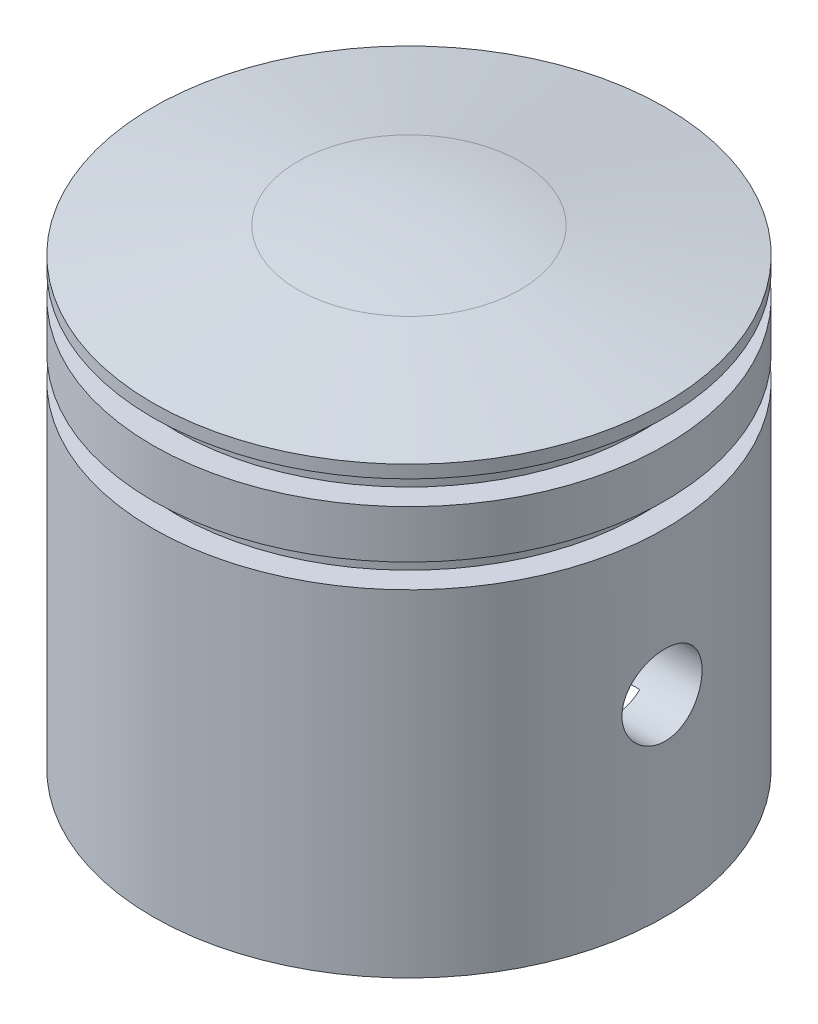
SolidWorks part; units mm, degrees
ref_plane "Front Plane" through (0, 0, 0) normal (0, 0, 1) x (1, 0, 0)
ref_plane "Top Plane" through (0, 0, 0) normal (0, 1, 0) x (1, 0, 0)
ref_plane "Right Plane" through (0, 0, 0) normal (1, 0, 0) x (0, 0, -1)
sketch "Sketch1" plane through (0, 0, 0) normal (0, 0, 1) x (1, 0, 0)
  line L0 (0, 0) -> (16, 0)
  line L1 (16, 0) -> (16, 27.7958)
  line L4 (0, 30) -> (0, 0)
  line L5 (16, 27.7958) -> (6.9459, 29.3923)
  line L6 (0, 30) -> (27.23, 30) construction
  arc A0 (6.9459, 29.3923) -> (0, 30) centre (0, -10) ccw
  dimension "D3" = 10
  dimension "D4" = 40
  dimension "D1" = 30
  dimension "D2" = 16
revolve "Revolve2" add sketch "Sketch1" angle 360 about L4
sketch "Sketch2" plane through (0, 0, 0) normal (1, 0, 0) x (0, 0, -1)
  line L0 (0, 0) -> (0, 40.7538) construction
  line L1 (-16, 0) -> (16, 0) construction
  line L2 (14.5, 27) -> (19.6685, 27)
  line L3 (14.5, 27) -> (14.5, 25.5)
  line L4 (14.5, 25.5) -> (19.6685, 25.5)
  line L5 (19.6685, 27) -> (19.6685, 25.5)
  line L6 (14.5, 22.5) -> (19.6685, 22.5)
  line L7 (14.5, 22.5) -> (14.5, 21)
  line L8 (14.5, 21) -> (19.6685, 21)
  line L9 (19.6685, 22.5) -> (19.6685, 21)
  dimension "D1" = 1.5
  dimension "D2" = 3
  dimension "D3" = 1.5
  dimension "D4" = 21
  dimension "D5" = 14.5
  dimension "D6" = 14.5
revolve "Cut-Revolve1" cut sketch "Sketch2" angle 360 about L0
sketch "Sketch3" plane through (0, 0, 0) normal (0, -1, 0) x (1, 0, 0)
  circle A0 centre (0, 0) radius 10
  dimension "D1" = 20
extrude "Cut-Extrude1" cut sketch "Sketch3" against normal blind 24
sketch "Sketch6" plane through (0, 0, 0) normal (0, -1, 0) x (1, 0, 0)
  circle A0 centre (0, 0) radius 13
  dimension "D1" = 26
extrude "Cut-Extrude2" cut sketch "Sketch6" against normal blind 10
sketch "Sketch7" plane through (0, 0, 0) normal (1, 0, 0) x (0, 0, -1)
  circle A0 centre (0, 12) radius 2.5
  dimension "D1" = 5
  dimension "D2" = 12
extrude "Cut-Extrude3" cut sketch "Sketch7" against normal through all both and the other way through all
